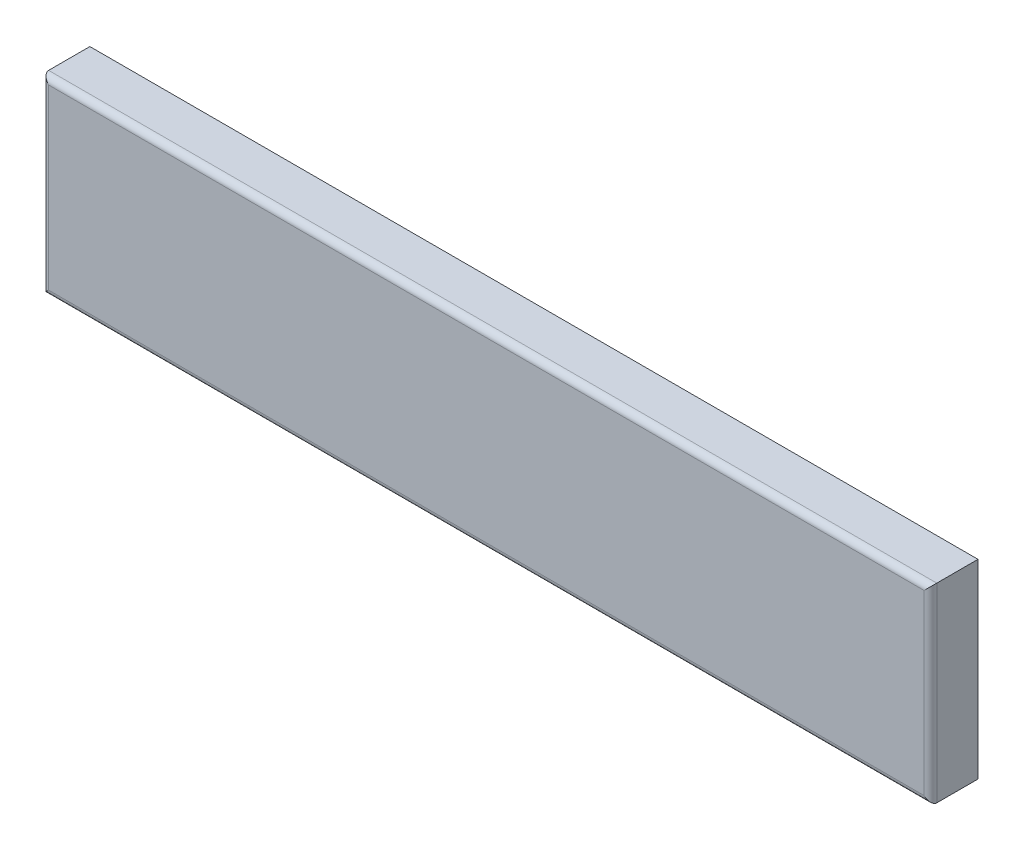
SolidWorks part; units mm, degrees
ref_plane "Front Plane" through (0, 0, 0) normal (0, 0, 1) x (1, 0, 0)
ref_plane "Top Plane" through (0, 0, 0) normal (0, 1, 0) x (1, 0, 0)
ref_plane "Right Plane" through (0, 0, 0) normal (1, 0, 0) x (0, 0, -1)
sketch "Sketch1" plane through (0, 0, 0) normal (0, 0, 1) x (1, 0, 0)
  line L1 (-177.8, -38.1) -> (177.8, -38.1)
  line L2 (-177.8, -38.1) -> (-177.8, 38.1)
  line L3 (-177.8, 38.1) -> (177.8, 38.1)
  line L4 (177.8, -38.1) -> (177.8, 38.1)
  line L5 (-177.8, -38.1) -> (177.8, 38.1) construction
  line L6 (-177.8, 38.1) -> (177.8, -38.1) construction
  point P0 (0, 0)
  dimension "D1" = 76.2
  dimension "D2" = 355.6
extrude "Boss-Extrude1" add sketch "Sketch1" along normal blind 2.54
sketch "Sketch2" plane through (0, 0, 2.54) normal (0, 0, 1) x (1, 0, 0)
  line L0 (175.26, 35.56) -> (-175.26, 35.56)
  line L1 (-175.26, 35.56) -> (-175.26, -35.56)
  line L2 (-175.26, -35.56) -> (175.26, -35.56)
  line L3 (175.26, -35.56) -> (175.26, 35.56)
  line L4 (177.8, -38.1) -> (177.8, 38.1)
  line L5 (177.8, 38.1) -> (-177.8, 38.1)
  line L6 (-177.8, 38.1) -> (-177.8, -38.1)
  line L7 (-177.8, -38.1) -> (177.8, -38.1)
  line L8 (177.8, -38.1) -> (177.8, 38.1)
  line L9 (177.8, 38.1) -> (-177.8, 38.1)
  line L10 (-177.8, 38.1) -> (-177.8, -38.1)
  line L11 (-177.8, -38.1) -> (177.8, -38.1)
  dimension "D1" = 0
  dimension "D2" = 2.54
extrude "Boss-Extrude2" add sketch "Sketch2" against normal blind 19.05
fillet "Fillet1" radius 2.54 4 edges at (0, -38.1, 2.54) (-177.8, 0, 2.54) (0, 38.1, 2.54) (177.8, 0, 2.54)
